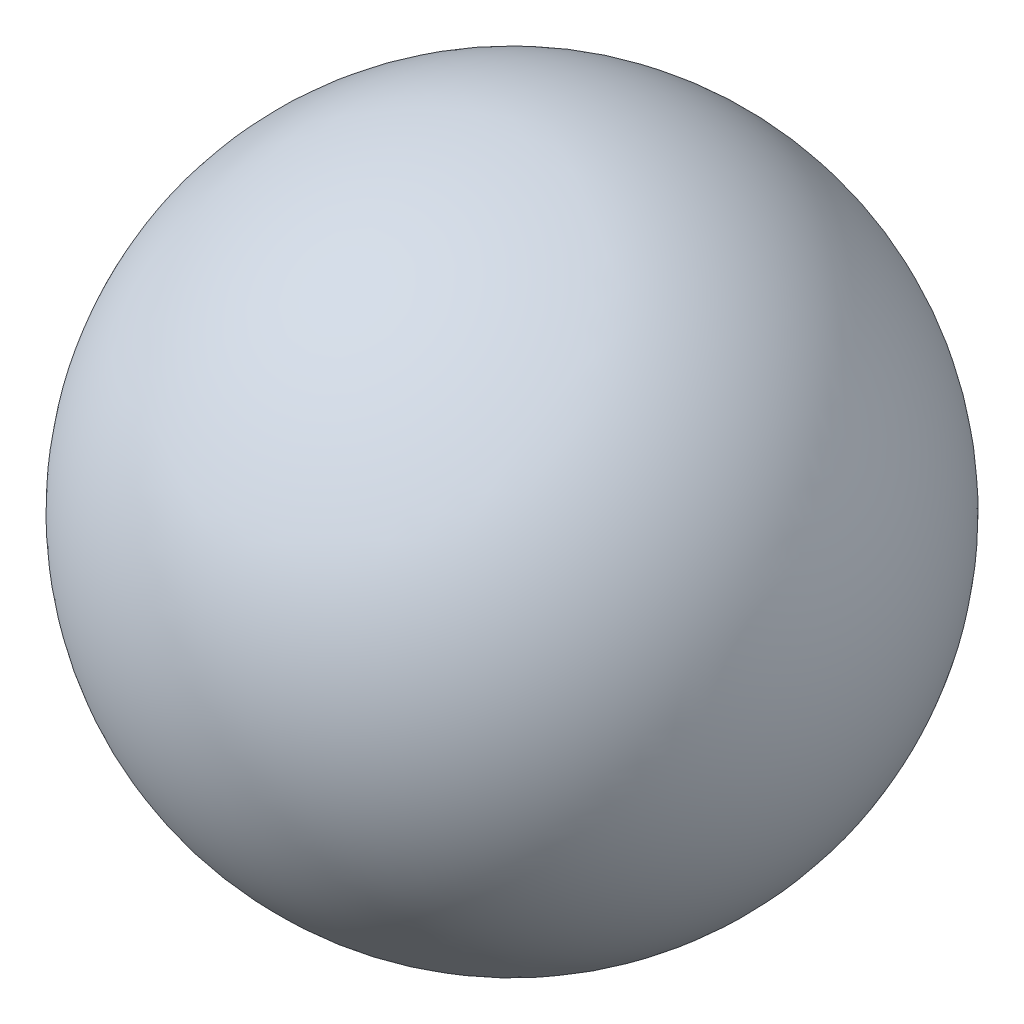
SolidWorks part; units mm, degrees
ref_plane "Front Plane" through (0, 0, 0) normal (0, 0, 1) x (1, 0, 0)
ref_plane "Top Plane" through (0, 0, 0) normal (0, 1, 0) x (1, 0, 0)
ref_plane "Right Plane" through (0, 0, 0) normal (1, 0, 0) x (0, 0, -1)
sketch "Sketch3" plane through (0, 0, 0) normal (0, 1, 0) x (1, 0, 0)
  line L0 (-19.05, 0) -> (19.05, 0)
  arc A0 (19.05, 0) -> (-19.05, 0) centre (0, 0) ccw
  dimension "D1" = 19.05
revolve "Revolve2" add sketch "Sketch3" angle 360 about L0
